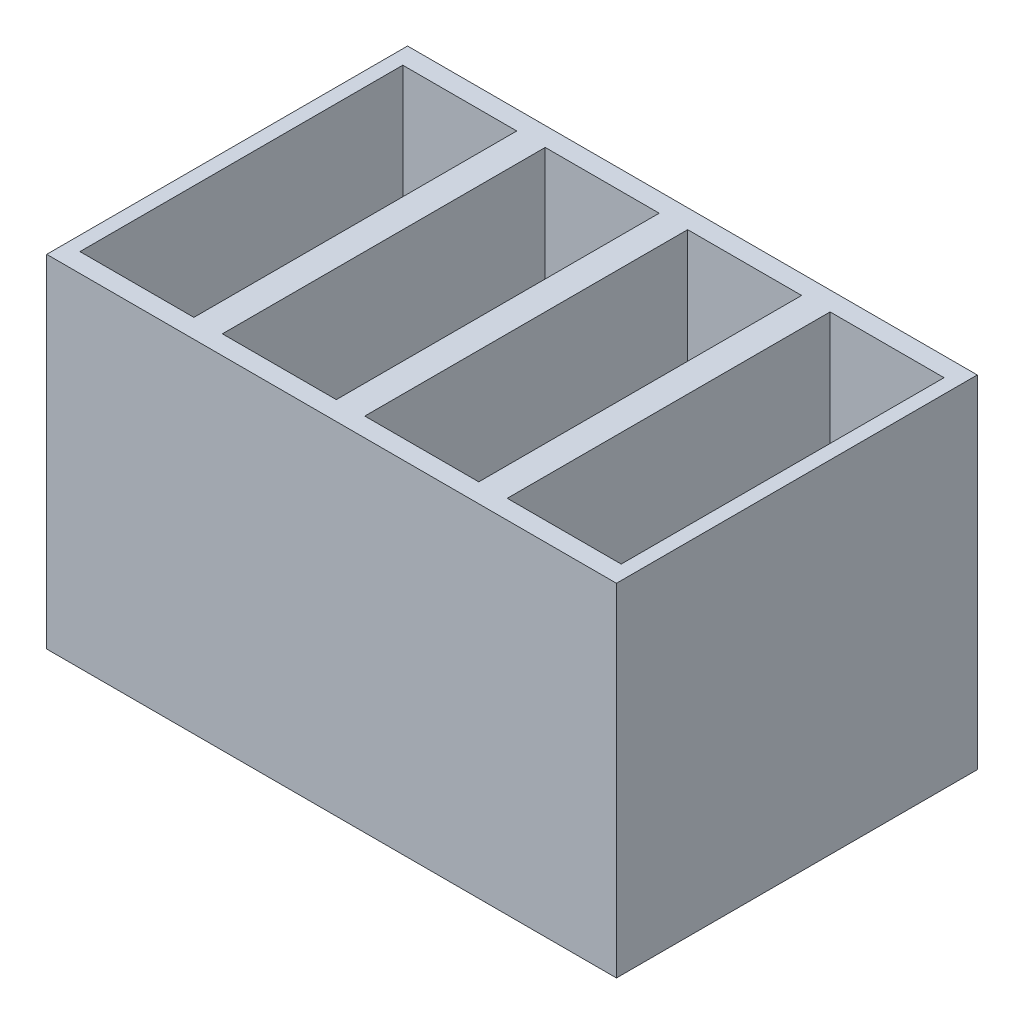
SolidWorks part; units mm, degrees
ref_plane "Front Plane" through (0, 0, 0) normal (0, 0, 1) x (1, 0, 0)
ref_plane "Top Plane" through (0, 0, 0) normal (0, 1, 0) x (1, 0, 0)
ref_plane "Right Plane" through (0, 0, 0) normal (1, 0, 0) x (0, 0, -1)
sketch "Sketch1" plane through (0, 0, 0) normal (0, 1, 0) x (1, 0, 0)
  line L0 (-1066.8, 482.6) -> (-1066.8, -482.6) construction
  line L1 (-1828.8, 482.6) -> (-304.8, 482.6)
  line L2 (-1828.8, 482.6) -> (-1828.8, -482.6)
  line L3 (-1828.8, -482.6) -> (-304.8, -482.6)
  line L4 (-304.8, 482.6) -> (-304.8, -482.6)
  line L5 (-1790.7, 0) -> (-1485.9, 0) construction
  line L6 (-1790.7, 431.8) -> (-1485.9, 431.8)
  line L7 (-1790.7, 431.8) -> (-1790.7, -431.8)
  line L8 (-1790.7, -431.8) -> (-1485.9, -431.8)
  line L9 (-1485.9, 431.8) -> (-1485.9, -431.8)
  line L10 (-1409.7, 431.8) -> (-1409.7, -431.8)
  line L11 (-1409.7, 431.8) -> (-1104.9, 431.8)
  line L12 (-1104.9, 431.8) -> (-1104.9, -431.8)
  line L13 (-1409.7, -431.8) -> (-1104.9, -431.8)
  line L14 (-1028.7, 431.8) -> (-1028.7, -431.8)
  line L15 (-1028.7, 431.8) -> (-723.9, 431.8)
  line L16 (-723.9, 431.8) -> (-723.9, -431.8)
  line L17 (-1028.7, -431.8) -> (-723.9, -431.8)
  line L18 (-647.7, 431.8) -> (-647.7, -431.8)
  line L19 (-647.7, 431.8) -> (-342.9, 431.8)
  line L20 (-342.9, 431.8) -> (-342.9, -431.8)
  line L21 (-647.7, -431.8) -> (-342.9, -431.8)
  line L22 (0, 1277.468) -> (0, -1043.2112) construction
  point P6 (-1066.8, 0)
  point P14 (-1638.3, 0)
  dimension "D1" = 1524
  dimension "D2" = 965.2
  dimension "D3" = 304.8
  dimension "D4" = 863.6
  dimension "D5" = 38.1
  dimension "D6" = 4
  dimension "D7" = 304.8
extrude "Boss-Extrude2" add sketch "Sketch1" along normal blind 914.4
